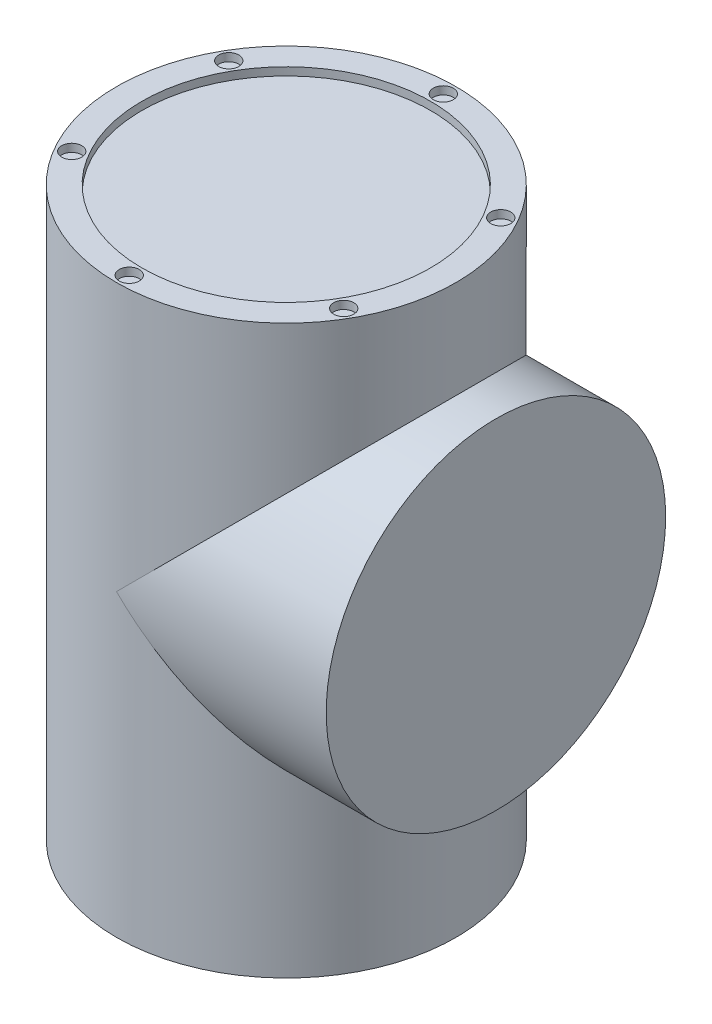
SolidWorks part; units mm, degrees
ref_plane "Alzado" through (0, 0, 0) normal (0, 0, 1) x (1, 0, 0)
ref_plane "Planta" through (0, 0, 0) normal (0, 1, 0) x (1, 0, 0)
ref_plane "Vista lateral" through (0, 0, 0) normal (1, 0, 0) x (0, 0, -1)
sketch "Croquis1" plane through (0, 0, 0) normal (0, 1, 0) x (1, 0, 0)
  circle A0 centre (0, 0) radius 42.5
  dimension "D1" = 85
extrude "Saliente-Extruir1" add sketch "Croquis1" along normal blind 140
sketch "Croquis2" plane through (0, 0, 0) normal (1, 0, 0) x (0, 0, -1)
  line L0 (42.5, 140) -> (-42.5, 140) construction
  line L2 (42.5, 0) -> (42.5, 140) construction
  circle A0 centre (0, 75) radius 42.5
  dimension "D1" = 85
  dimension "D2" = 65
  dimension "D3" = 42.5
extrude "Saliente-Extruir2" add sketch "Croquis2" along normal blind 52.5
sketch "Croquis3" plane through (0, 140, 0) normal (0, 1, 0) x (1, 0, 0)
  circle A0 centre (0, 0) radius 42.5
  circle A1 centre (0, 0) radius 36.1436
  circle A2 centre (0, 39.3191) radius 2.5082
  circle A3 centre (34.0513, 19.6595) radius 2.5082
  circle A4 centre (34.0513, -19.6595) radius 2.5082
  circle A5 centre (0, -39.3191) radius 2.5082
  circle A6 centre (-34.0513, -19.6595) radius 2.5082
  circle A7 centre (-34.0513, 19.6595) radius 2.5082
  point P18 (0, 0)
  dimension "D1" = 6
extrude "Saliente-Extruir3" add sketch "Croquis3" along normal blind 2
